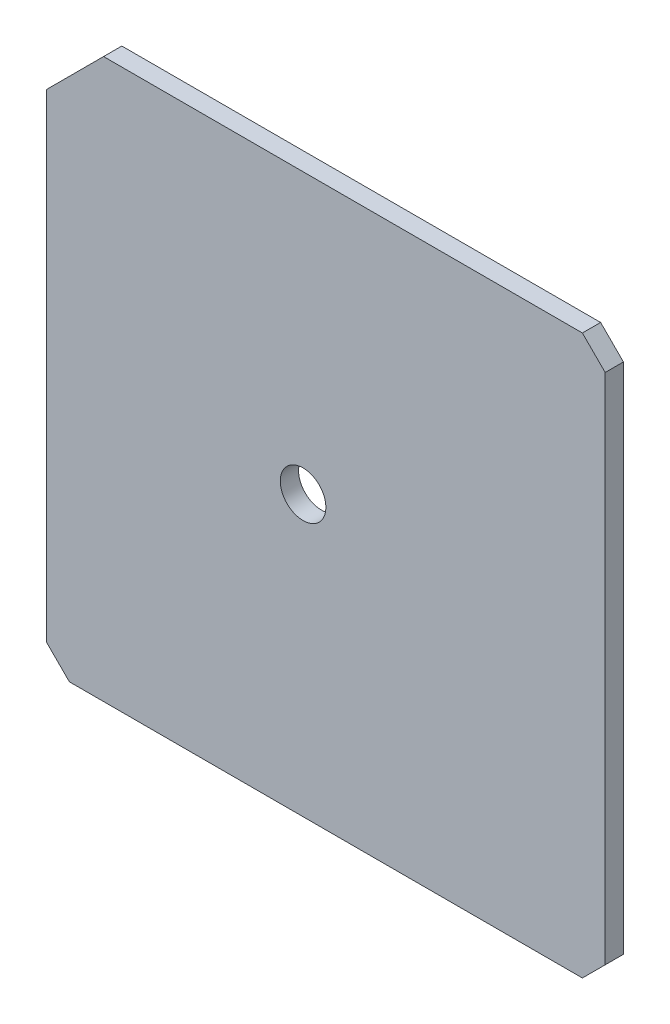
SolidWorks part; units mm, degrees
material "A-Glass Fiber"
ref_plane "Front Plane" through (0, 0, 0) normal (1, 0, 0) x (0, 1, 0)
ref_plane "Top Plane" through (0, 0, 0) normal (0, 0, 1) x (0, 1, 0)
ref_plane "Right Plane" through (0, 0, 0) normal (0, 1, 0) x (-1, 0, 0)
sketch "Sketch1" plane through (0, 0, 0) normal (0, 0, 1) x (0, 1, 0)
  line L1 (0, 0) -> (49, 0)
  line L2 (0, 0) -> (0, 49)
  line L3 (0, 49) -> (49, 49)
  line L4 (49, 0) -> (49, 49)
  circle A0 centre (24.5, 26.5) radius 2
  dimension "D2" = 4
  dimension "D1" = 49
  dimension "D3" = 24.5
  dimension "D4" = 22.5
extrude "Boss-Extrude1" add sketch "Sketch1" against normal blind 1.6
chamfer "Chamfer1" distance 5 angle 45 1 edges at (-49, 49, -0.8)
chamfer "Chamfer2" distance 2 angle 45 3 edges at (0, 49, -0.8) (0, 0, -0.8) (-49, 0, -0.8)
